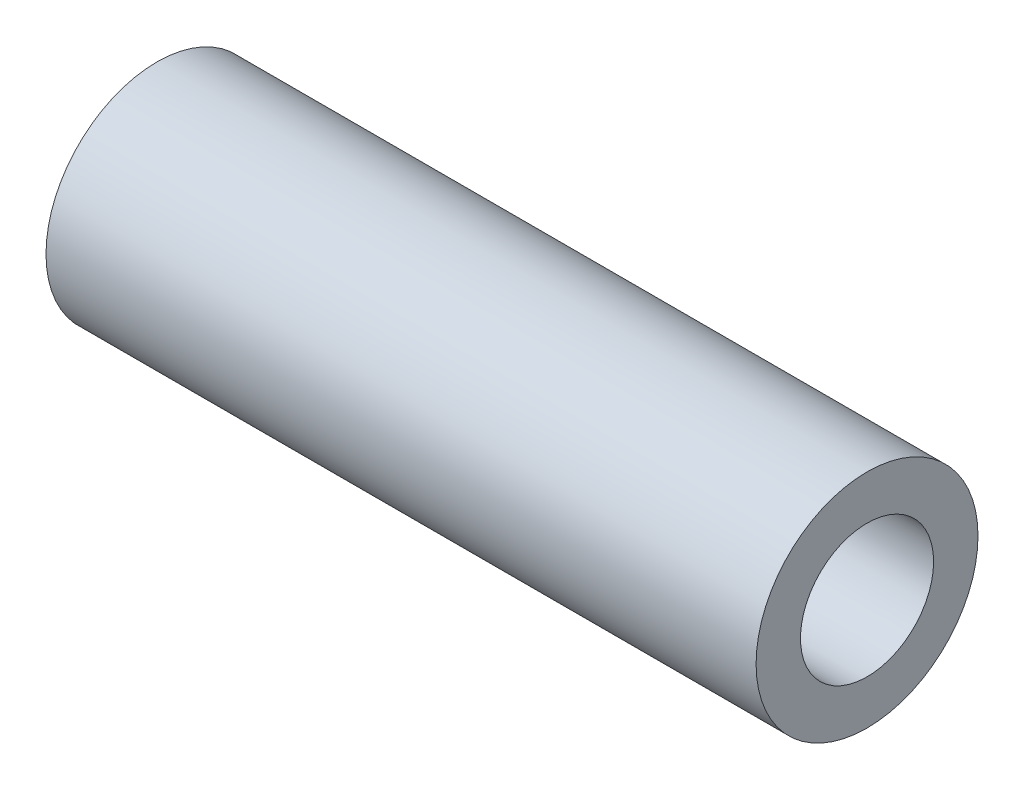
SolidWorks part; units mm, degrees
material "Thornel Mat VMA"
ref_plane "Front Plane" through (0, 0, 0) normal (0, 0, 1) x (1, 0, 0)
ref_plane "Top Plane" through (0, 0, 0) normal (0, 1, 0) x (1, 0, 0)
ref_plane "Right Plane" through (0, 0, 0) normal (1, 0, 0) x (0, 0, -1)
sketch "Sketch1" plane through (0, 0, 0) normal (1, 0, 0) x (0, 0, -1)
  circle A0 centre (0, 0) radius 4.7625
  circle A1 centre (0, 0) radius 7.9375
  dimension "D1" = 9.525
  dimension "D2" = 15.875
extrude "Boss-Extrude1" add sketch "Sketch1" along normal mid plane 50.8
